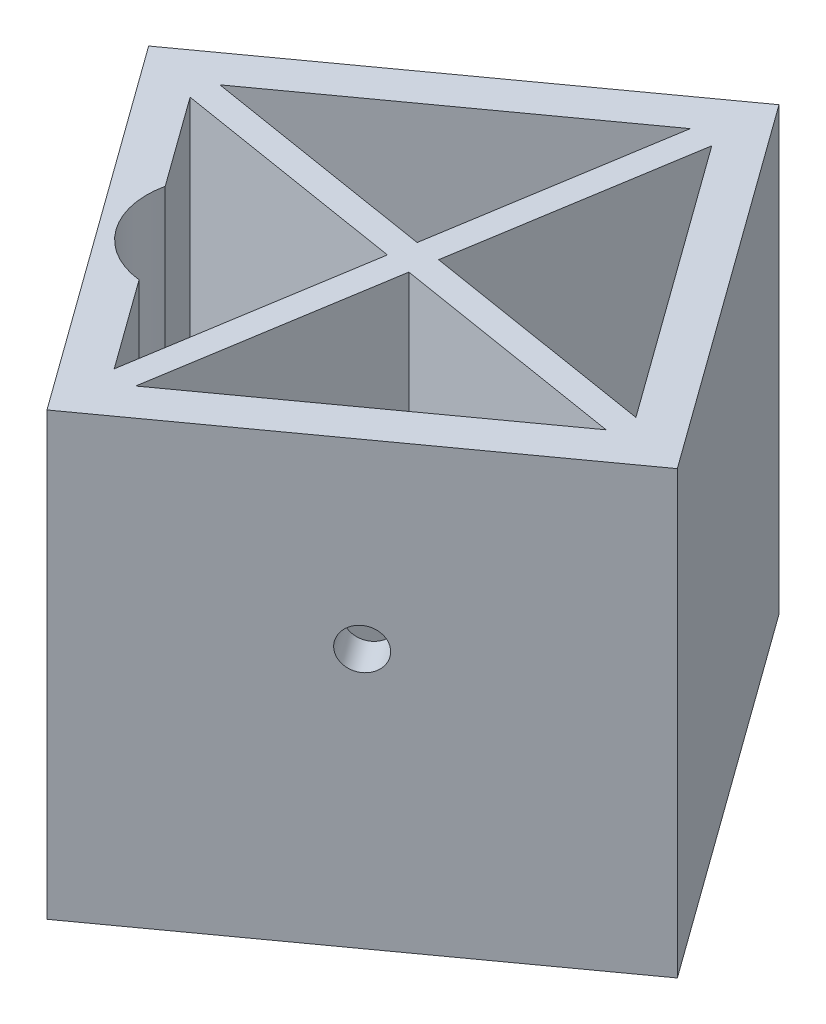
SolidWorks part; units mm, degrees
ref_plane "Front Plane" through (0, 0, 0) normal (0, 0, 1) x (1, 0, 0)
ref_plane "Top Plane" through (0, 0, 0) normal (0, 1, 0) x (1, 0, 0)
ref_plane "Right Plane" through (0, 0, 0) normal (1, 0, 0) x (0, 0, -1)
sketch "Sketch1" plane through (0, 0, 0) normal (0, 1, 0) x (1, 0, 0)
  line L0 (0, 82.55) -> (0, -82.55) construction
  line L1 (-107.95, 82.55) -> (107.95, 82.55) construction
  line L2 (-114.3, -82.55) -> (114.3, -82.55) construction
  line L3 (-124.3737, -76.1961) -> (-111.4355, -94.1105)
  line L4 (-111.4355, -94.1105) -> (-93.5211, -81.1723)
  line L5 (-93.5211, -81.1723) -> (-106.4593, -63.2579)
  line L6 (-106.4593, -63.2579) -> (-124.3737, -76.1961)
  line L7 (-114.3, -82.55) -> (-119.6867, -86.4404) construction
  line L8 (-105.0715, -106.6767) -> (-134.3018, -66.204) construction
  line L9 (-106.0875, -60.9529) -> (-126.6787, -75.8243) construction
  line L10 (-126.6787, -75.8243) -> (-111.8073, -96.4156) construction
  line L11 (-111.8073, -96.4156) -> (-91.216, -81.5441) construction
  line L12 (-91.216, -81.5441) -> (-106.0875, -60.9529) construction
  circle A0 centre (0, 0) radius 147.6375 construction
  circle A1 centre (-107.95, 82.55) radius 1.5
  circle A2 centre (107.95, 82.55) radius 1.5
  circle A3 centre (114.3, -82.55) radius 1.5
  circle A4 centre (-114.3, -82.55) radius 1.5
  dimension "D1" = 295.275
  dimension "D5" = 3
  dimension "D2" = 215.9
  dimension "D3" = 228.6
  dimension "D4" = 165.1
  dimension "D6" = 22.098
  dimension "D7" = 25.4
extrude "Boss-Extrude2" add sketch "Sketch1" along normal blind 2.54 contours L5 L6 L3 L4 A4
sketch "Sketch2" plane through (0, 2.54, 0) normal (0, 1, 0) x (1, 0, 0)
  line L0 (-106.8883, -65.9176) -> (-121.714, -76.6251)
  line L1 (-121.714, -76.6251) -> (-118.0222, -81.7368)
  line L2 (-111.0065, -91.4508) -> (-96.1808, -80.7433)
  line L3 (-96.1808, -80.7433) -> (-106.8883, -65.9176)
  line L4 (-124.3737, -76.1961) -> (-111.4355, -94.1105) construction
  line L5 (-93.5211, -81.1723) -> (-106.4593, -63.2579) construction
  line L6 (-106.4593, -63.2579) -> (-124.3737, -76.1961) construction
  line L7 (-111.4355, -94.1105) -> (-93.5211, -81.1723) construction
  line L8 (-106.4593, -63.2579) -> (-124.3737, -76.1961)
  line L9 (-124.3737, -76.1961) -> (-111.4355, -94.1105)
  line L10 (-111.4355, -94.1105) -> (-93.5211, -81.1723)
  line L11 (-93.5211, -81.1723) -> (-106.4593, -63.2579)
  line L12 (-114.6983, -86.3391) -> (-111.0065, -91.4508)
  line L13 (-121.714, -76.6251) -> (-111.0065, -91.4508) construction
  arc A0 (-118.0222, -81.7368) -> (-114.6983, -86.3391) centre (-114.3, -82.55) ccw
  dimension "D3" = 7.62
  dimension "D2" = 1.905
extrude "Boss-Extrude3" add sketch "Sketch2" along normal blind 19.05
sketch "Sketch3" plane through (0, 21.59, 0) normal (0, 1, 0) x (1, 0, 0)
  line L0 (-124.3737, -76.1961) -> (-93.5211, -81.1723) construction
  line L1 (-106.4593, -63.2579) -> (-111.4355, -94.1105) construction
  line L2 (-111.4355, -94.1105) -> (-93.5211, -81.1723) construction
  line L3 (-124.4748, -76.823) -> (-93.6222, -81.7992)
  line L4 (-107.0862, -63.1568) -> (-112.0624, -94.0094)
  line L5 (-124.2726, -75.5692) -> (-93.42, -80.5454)
  line L6 (-105.8324, -63.3591) -> (-110.8086, -94.2116)
  dimension "D1" = 0.635
extrude "Boss-Extrude6" add sketch "Sketch3" against normal up to surface (19.05 mm away) up to face at (-111.5897, 2.54, 80.5926)
sketch "Sketch4" plane through (6.4691, 0, 8.9572) normal (0.5855, 0, 0.8107) x (0.8107, 0, -0.5855)
  line L0 (-134.3902, 0) -> (-134.3902, 12.7) construction
  line L2 (-145.4392, 0) -> (-123.3412, 0) construction
  circle A0 centre (-134.3902, 12.7) radius 1
  dimension "D2" = 2
  dimension "D1" = 12.7
extrude "Cut-Extrude1" cut sketch "Sketch4" against normal through all
fillet "Fillet1" radius 6.35 2 edges at (-114.3011, 2.54, 71.2714) (-103.5937, 2.54, 86.0971)
ref_plane "Plane1" through (0, 0, 0) normal (-0.5855, 0, -0.8107) x (-0.8107, 0, 0.5855)
sketch "Sketch5" plane through (0, 0, 0) normal (-0.5855, 0, -0.8107) x (-0.8107, 0, 0.5855)
  line L0 (123.3412, 0) -> (145.4392, 0)
  line L1 (145.4392, 0) -> (145.4392, -1.5452)
  line L2 (145.4392, -1.5452) -> (123.3412, 0)
  dimension "D1" = 4
extrude "Boss-Extrude7" [suppressed] add sketch "Sketch5" along normal mid plane 25.4
sketch "Sketch6" [suppressed] plane through (0, 2.54, 0) normal (0, 1, 0) x (1, 0, 0)
  circle A0 centre (-114.3, -82.55) radius 1.5 construction
  circle A1 centre (-114.3, -82.55) radius 1.5
extrude "Cut-Extrude2" [suppressed] cut sketch "Sketch6" against normal through all
